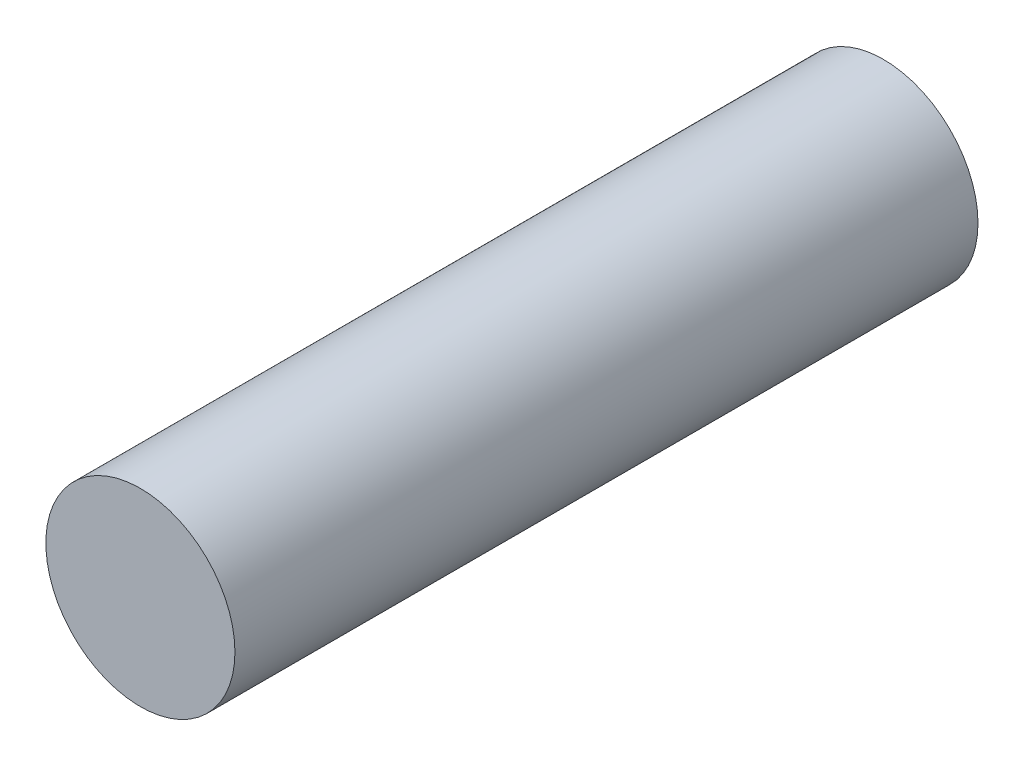
SolidWorks part; units mm, degrees
ref_plane "Front Plane" through (0, 0, 0) normal (0, 0, 1) x (1, 0, 0)
ref_plane "Top Plane" through (0, 0, 0) normal (0, 1, 0) x (1, 0, 0)
ref_plane "Right Plane" through (0, 0, 0) normal (1, 0, 0) x (0, 0, -1)
sketch "Sketch2" plane through (0, 0, 0) normal (0, 0, 1) x (1, 0, 0)
  circle A0 centre (0, 0) radius 0.7
  dimension "D1" = 1.4
extrude "Boss-Extrude1" add sketch "Sketch2" along normal blind 5.5013
